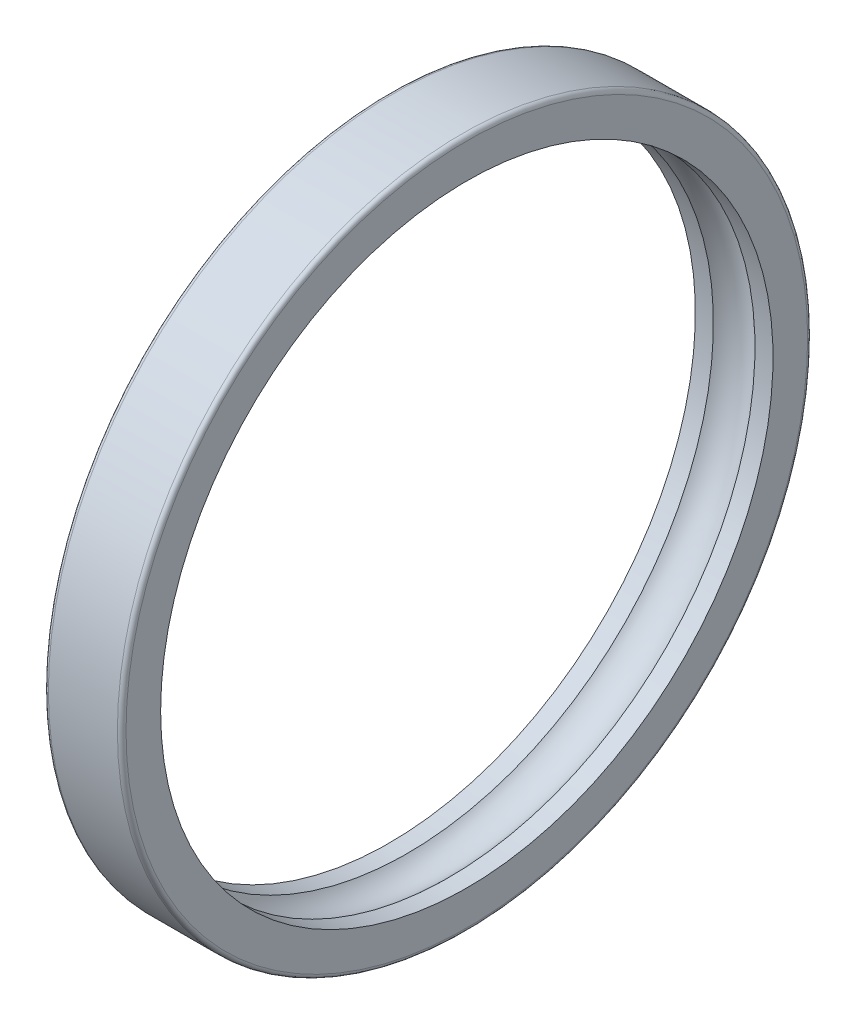
SolidWorks part; units mm, degrees
ref_plane "Piano frontale" through (0, 0, 0) normal (0, 0, 1) x (1, 0, 0)
ref_plane "Piano superiore" through (0, 0, 0) normal (0, 1, 0) x (1, 0, 0)
ref_plane "Piano destro" through (0, 0, 0) normal (1, 0, 0) x (0, 0, -1)
ref_plane "Piano1" through (0, 0, 0) normal (0, 0, 1) x (1, 0, 0)
sketch "Schizzo1" plane through (0, 0, 0) normal (0, 0, 1) x (1, 0, 0)
  line L0 (0, 79) -> (0, 70.975)
  line L1 (0, 70.975) -> (4.1837, 70.975)
  line L2 (13.8163, 70.975) -> (18, 70.975)
  line L3 (18, 70.975) -> (18, 79)
  line L4 (17, 80) -> (1, 80)
  line L5 (200, 0) -> (-200, 0) construction
  arc A0 (4.1837, 70.975) -> (13.8163, 70.975) centre (9, 66.25) cw
  arc A1 (18, 79) -> (17, 80) centre (17, 79) ccw
  arc A2 (1, 80) -> (0, 79) centre (1, 79) ccw
revolve "Rivoluzione1" add sketch "Schizzo1" angle 360 about L5
